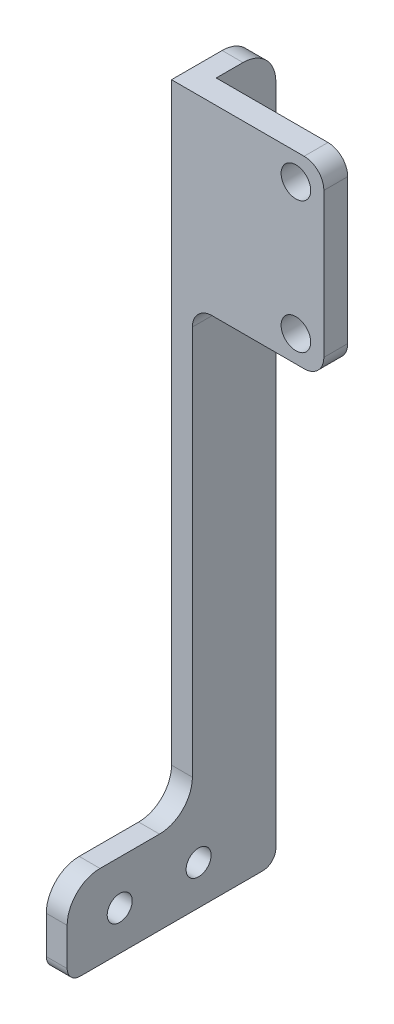
SolidWorks part; units mm, degrees
ref_plane "Front Plane" through (0, 0, 0) normal (0, 0, 1) x (1, 0, 0)
ref_plane "Top Plane" through (0, 0, 0) normal (0, 1, 0) x (1, 0, 0)
ref_plane "Right Plane" through (0, 0, 0) normal (1, 0, 0) x (0, 0, -1)
sketch "Sketch2" plane through (0, 0, 0) normal (1, 0, 0) x (0, 0, -1)
  line L0 (0, 0) -> (0, -101.6552) construction
  line L1 (0, -101.6552) -> (-25.4, -101.6552) construction
  line L3 (-25.4, -95.3052) -> (-6.35, -95.3052)
  line L4 (-6.35, -95.3052) -> (-6.35, 0) construction
  line L5 (-6.35, 0) -> (6.35, 0)
  line L6 (6.35, 0) -> (6.35, -108.0052)
  line L7 (6.35, -108.0052) -> (-25.4, -108.0052)
  line L9 (-25.4, -108.0052) -> (-25.4, -95.3052)
  line L12 (-6.35, -95.3052) -> (-6.35, 0)
  point P12 (0, 0)
  dimension "D5" = 12.7
  dimension "D1" = 101.6552
  dimension "D2" = 31.75
extrude "Boss-Extrude1" add sketch "Sketch2" against normal blind 3.175
fillet "Fillet1" radius 5 3 edges at (-1.5875, 0, -6.35) (-1.5875, -95.3052, 25.4) (-1.5875, -95.3052, 6.35)
sketch "Sketch3" plane through (0, 0, 0) normal (1, 0, 0) x (0, 0, -1)
  line L0 (-6.35, 0) -> (-6.35, -28)
  line L1 (-6.35, -28) -> (-2.7202, -28)
  line L2 (-2.7202, -28) -> (-2.7202, 0)
  line L3 (-2.7202, 0) -> (-6.35, 0)
  dimension "D1" = 3.6298
  dimension "D2" = 28
extrude "Boss-Extrude2" add sketch "Sketch3" along normal blind 20
ref_plane "Plane1" through (0, 0, 2.7202) normal (0, 0, -1) x (-1, 0, 0)
sketch "Sketch4" plane through (0, 0, 2.7202) normal (0, 0, -1) x (-1, 0, 0)
  line L0 (-15.75, -14) -> (0, -14) construction
  line L1 (-15.75, -24) -> (-15.75, -4) construction
  line L4 (0, -28) -> (0, 0)
  line L5 (0, 0) -> (-20, 0)
  line L6 (-20, 0) -> (-20, -28)
  line L7 (-20, -28) -> (0, -28)
  line L8 (0, -28) -> (0, 0)
  line L9 (0, 0) -> (-20, 0)
  line L10 (-20, 0) -> (-20, -28)
  line L11 (-20, -28) -> (0, -28)
  circle A0 centre (-15.75, -24) radius 2.25
  circle A1 centre (-15.75, -4) radius 2.25
  circle A2 centre (-15.75, -4) radius 4.25 construction
  dimension "D2" = 4.5
  dimension "D4" = 2
  dimension "D3" = 20
  dimension "D1" = 0
extrude "Cut-Extrude1" cut sketch "Sketch4" against normal up to surface (3.6298 mm away) contours A0 | A1 up to face at (5.6083, -39.4351, 6.35)
fillet "Fillet2" radius 3 3 edges at (20, 0, 4.5351) (20, -28, 4.5351) (0, -28, 4.5351)
fillet "Fillet3" radius 2 2 edges at (-1.5875, -108.0052, 25.4) (-1.5875, -108.0052, -6.35)
sketch "Sketch6" plane through (0, 0, 0) normal (1, 0, 0) x (0, 0, -1)
  line L8 (-25.4, -100.3052) -> (-25.4, -106.0052)
  line L9 (-23.4, -108.0052) -> (4.35, -108.0052)
  line L10 (6.35, -106.0052) -> (6.35, -5)
  line L11 (1.35, 0) -> (-2.7202, 0)
  line L12 (-2.7202, 0) -> (-2.7202, -31)
  line L13 (-2.7202, -31) -> (-6.35, -31)
  line L14 (-6.35, -31) -> (-6.35, -90.3052)
  line L15 (-11.35, -95.3052) -> (-20.4, -95.3052)
  line L16 (-25.4, -100.3052) -> (-25.4, -106.0052)
  line L17 (-23.4, -108.0052) -> (4.35, -108.0052)
  line L18 (6.35, -106.0052) -> (6.35, -5)
  line L19 (1.35, 0) -> (-2.7202, 0)
  line L20 (-2.7202, 0) -> (-2.7202, -31)
  line L21 (-2.7202, -31) -> (-6.35, -31)
  line L22 (-6.35, -31) -> (-6.35, -90.3052)
  line L23 (-11.35, -95.3052) -> (-20.4, -95.3052)
  circle A0 centre (-5.4056, -102.0052) radius 1.9 construction
  circle A1 centre (-5.4056, -102.0052) radius 1.9
  circle A2 centre (-17.4056, -102.0052) radius 1.9 construction
  circle A3 centre (-17.4056, -102.0052) radius 1.9
  arc A5 (-25.4, -106.0052) -> (-23.4, -108.0052) centre (-23.4, -106.0052) ccw
  arc A6 (4.35, -108.0052) -> (6.35, -106.0052) centre (4.35, -106.0052) ccw
  arc A7 (6.35, -5) -> (1.35, 0) centre (1.35, -5) ccw
  arc A8 (-11.35, -95.3052) -> (-6.35, -90.3052) centre (-11.35, -90.3052) ccw
  arc A9 (-20.4, -95.3052) -> (-25.4, -100.3052) centre (-20.4, -100.3052) ccw
  arc A10 (-25.4, -106.0052) -> (-23.4, -108.0052) centre (-23.4, -106.0052) ccw
  arc A11 (4.35, -108.0052) -> (6.35, -106.0052) centre (4.35, -106.0052) ccw
  arc A12 (6.35, -5) -> (1.35, 0) centre (1.35, -5) ccw
  arc A13 (-11.35, -95.3052) -> (-6.35, -90.3052) centre (-11.35, -90.3052) ccw
  arc A14 (-20.4, -95.3052) -> (-25.4, -100.3052) centre (-20.4, -100.3052) ccw
  dimension "D1" = 0
extrude "Cut-Extrude2" cut sketch "Sketch6" against normal up to surface (3.175 mm away) contours L16 A3 | A1
